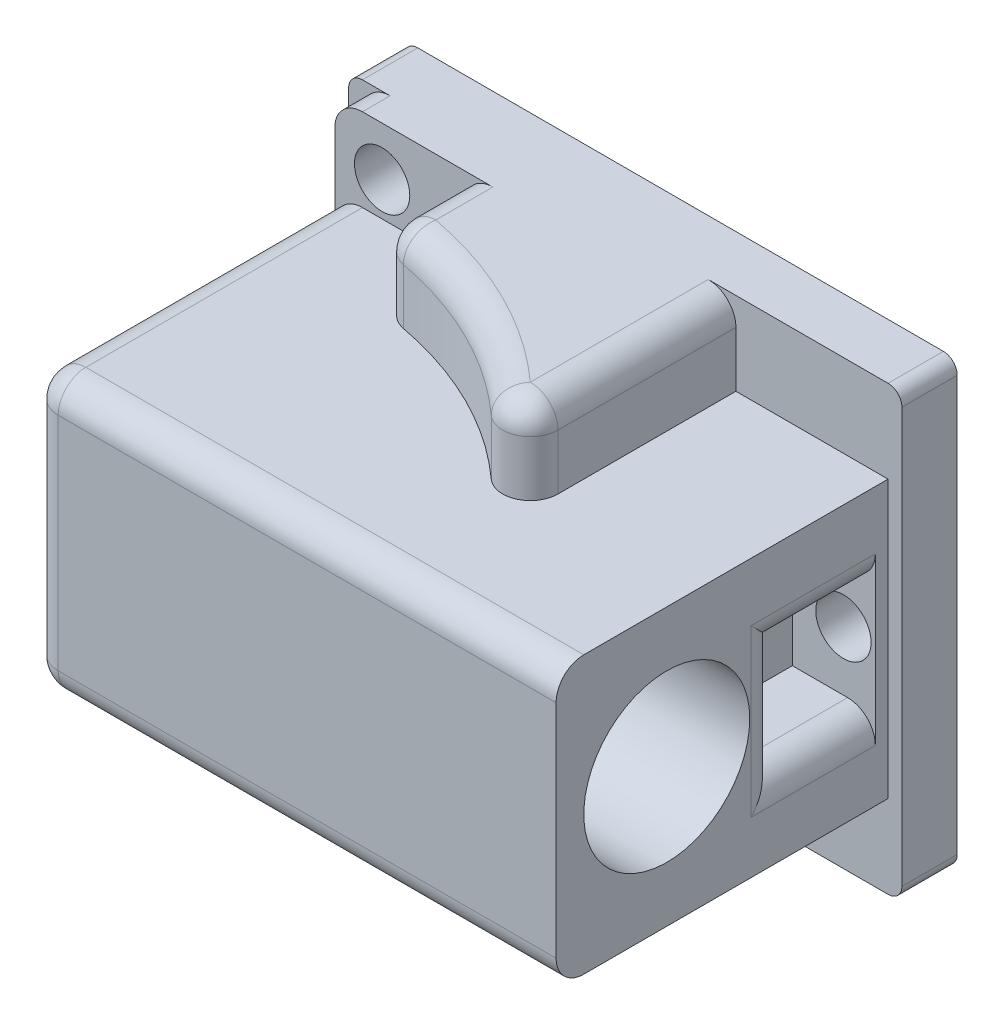
SolidWorks part; units mm, degrees
ref_plane "Front Plane" through (0, 0, 0) normal (0, 0, 1) x (1, 0, 0)
ref_plane "Top Plane" through (0, 0, 0) normal (0, 1, 0) x (1, 0, 0)
ref_plane "Right Plane" through (0, 0, 0) normal (1, 0, 0) x (0, 0, -1)
ref_plane "Plane1" through (0, 50, 0) normal (0, 1, 0) x (1, 0, 0)
sketch "Sketch1" plane through (0, 50, 0) normal (0, 1, 0) x (1, 0, 0)
  line L0 (-95, 0) -> (-95, -110)
  line L1 (-95, -110) -> (40, -110)
  line L2 (40, -110) -> (40, 0)
  line L3 (40, 0) -> (-95, 0)
extrude "Boss-Extrude1" add sketch "Sketch1" against normal blind 100
sketch "Sketch2" plane through (0, 50, 0) normal (0, 1, 0) x (-1, 0, 0)
  line L0 (-40, 0) -> (-40, 110)
  line L1 (95, 61.9894) -> (95, 0)
  line L2 (95, 0) -> (-40, 0)
  arc A0 (-40, 110) -> (95, 61.9894) centre (63.8483, 188.2018) ccw
extrude "Boss-Extrude2" add sketch "Sketch2" along normal blind 30
sketch "Sketch3" plane through (0, -50, 0) normal (0, -1, 0) x (1, 0, 0)
  line L0 (40, 0) -> (-95, 0)
  line L1 (-95, 0) -> (-95, 61.9894)
  line L2 (40, 110) -> (40, 0)
  arc A0 (-95, 61.9894) -> (40, 110) centre (-63.8483, 188.2018) ccw
extrude "Boss-Extrude3" add sketch "Sketch3" along normal blind 30
sketch "Sketch4" plane through (0, 0, 110) normal (0, 0, 1) x (1, 0, 0)
  line L0 (40, -50) -> (-95, -50)
  line L1 (-95, -50) -> (-95, 50)
  line L2 (-95, 50) -> (40, 50)
  line L3 (40, 50) -> (40, -50)
extrude "Boss-Extrude4" add sketch "Sketch4" along normal blind 30
sketch "Sketch5" plane through (40, 0, 0) normal (1, 0, 0) x (0, 0, -1)
  line L0 (-140, 50) -> (-20, 50)
  line L1 (-20, 50) -> (-20, 80)
  line L2 (-20, 80) -> (0, 80)
  line L3 (0, 80) -> (0, -80)
  line L4 (0, -80) -> (-20, -80)
  line L5 (-20, -80) -> (-20, -50)
  line L6 (-20, -50) -> (-140, -50)
  line L7 (-140, -50) -> (-140, 50)
extrude "Boss-Extrude5" add sketch "Sketch5" along normal blind 55
sketch "Sketch6" plane through (-95, 0, 0) normal (-1, 0, 0) x (0, 0, 1)
  line L0 (0, -80) -> (0, 80)
  line L1 (0, 80) -> (20, 80)
  line L2 (20, 80) -> (20, -80)
  line L3 (20, -80) -> (0, -80)
extrude "Boss-Extrude6" add sketch "Sketch6" along normal blind 5
sketch "Sketch7" plane through (95, 0, 0) normal (1, 0, 0) x (0, 0, -1)
  line L0 (-20, -80) -> (-20, 80)
  line L1 (-20, 80) -> (0, 80)
  line L2 (0, 80) -> (0, -80)
  line L3 (0, -80) -> (-20, -80)
extrude "Boss-Extrude7" add sketch "Sketch7" along normal blind 5
sketch "Sketch8" plane through (0, 80, 0) normal (0, 1, 0) x (-1, 0, 0)
  line L0 (47.8742, 59.187) -> (47.8742, 30)
  line L1 (47.8742, 30) -> (95, 30)
  line L2 (95, 30) -> (95, 61.9894)
  arc A0 (95, 61.9894) -> (47.8742, 59.187) centre (63.8483, 188.2018) cw
extrude "Cut-Extrude1" cut sketch "Sketch8" against normal blind 30
sketch "Sketch9" plane through (0, -80, 0) normal (0, -1, 0) x (1, 0, 0)
  line L0 (-47.8742, 30) -> (-47.8742, 59.187)
  line L1 (-95, 61.9894) -> (-95, 30)
  line L2 (-95, 30) -> (-47.8742, 30)
  arc A0 (-47.8742, 59.187) -> (-95, 61.9894) centre (-63.8483, 188.2018) cw
extrude "Cut-Extrude2" cut sketch "Sketch9" against normal blind 30
sketch "Sketch10" plane through (95, 0, 0) normal (1, 0, 0) x (0, 0, -1)
  line L0 (-24.6023, -21.1021) -> (-24.6023, 18.8979)
  line L1 (-24.6023, 18.8979) -> (-59.6023, 18.8979)
  line L2 (-59.6023, 18.8979) -> (-59.6023, -21.1021)
  line L3 (-59.6023, -21.1021) -> (-24.6023, -21.1021)
extrude "Cut-Extrude3" cut sketch "Sketch10" against normal blind 30
hole_wizard "Hole1" positions "Sketch12" profile "Sketch11" legacy
sketch "Sketch12" plane through (0, 0, 0) normal (0, 0, -1) x (-1, 0, 0)
  point P0 (0, 0)
sketch "Sketch11" plane through (0, 0, 0) normal (1, 0, 0) x (0, 1, 0)
  line L0 (0, 0) -> (0, 135)
  line L1 (0, 135) -> (40, 135)
  line L2 (40, 135) -> (40, 0)
  line L3 (40, 0) -> (0, 0)
  line L4 (0, 110) -> (0, -10) construction
  dimension "Diameter" = 80
  dimension "Depth" = 135
hole_wizard "Hole2" positions "Sketch14" profile "Sketch13" legacy
sketch "Sketch14" plane through (95, 0, 0) normal (1, 0, 0) x (0, 0, -1)
  point P0 (-100, 0)
sketch "Sketch13" plane through (95, 0, 100) normal (0, 1, 0) x (0, 0, -1)
  line L0 (0, 0) -> (0, 55)
  line L1 (0, 55) -> (30, 55)
  line L2 (30, 55) -> (30, 0)
  line L3 (30, 0) -> (0, 0)
  line L4 (0, 110) -> (0, -10) construction
  dimension "Diameter" = 60
  dimension "Depth" = 55
hole_wizard "3/4 Clearance Hole1" positions "Sketch16" profile "Sketch15" hole size "3/4" standard "ANSI Inch"
sketch "Sketch16" plane through (0, 0, 24.6023) normal (0, 0, 1) x (1, 0, 0)
  point P0 (83.46, 0.37)
sketch "Sketch15" plane through (83.46, 0.37, 24.6023) normal (1, 0, 0) x (0, -1, 0)
  line L0 (0, 0) -> (0, 24.6023)
  line L1 (0, 24.6023) -> (10, 24.6023)
  line L2 (10, 24.6023) -> (10, 0)
  line L5 (10, 0) -> (0, 0)
  line L11 (0, -6.35) -> (0, 107.95) construction
  dimension "Thru Hole Dia." = 20
  dimension "Thru Hole Depth" = 24.6023
hole_wizard "3/4 Clearance Hole2" positions "Sketch18" profile "Sketch17" hole size "3/4" standard "ANSI Inch"
sketch "Sketch18" plane through (0, 0, 30) normal (0, 0, 1) x (1, 0, 0)
  point P0 (-77.8954, -62.3163)
  point P1 (-77.8954, 62.3163)
sketch "Sketch17" plane through (-77.8954, -62.3163, 30) normal (1, 0, 0) x (0, -1, 0)
  line L0 (0, 0) -> (0, 30)
  line L1 (0, 30) -> (10, 30)
  line L2 (10, 30) -> (10, 0)
  line L5 (10, 0) -> (0, 0)
  line L11 (0, -6.35) -> (0, 107.95) construction
  dimension "Thru Hole Dia." = 20
  dimension "Thru Hole Depth" = 30
fillet "Fillet1" radius 5 4 edges at (-100, 80, 10) (100, 80, 10) (100, -80, 10) (-100, -80, 10)
fillet "Fillet2" radius 10 20 edges at (-95, 50, 85) (0, 50, 140) (-95, -50, 85) (-95, -80, 25) (-95, 0, 140) (0, -50, 140) (40, 65, 110) (40, 80, 65) (-47.8742, 65, 59.187) (1.2274, 80, 75.6623) (-47.8742, 80, 44.5935) (95, -21.1021, 42.1023) (95, -1.1021, 59.6023) (95, 18.8979, 42.1023) (40, -65, 110) (40, -80, 65) (1.2274, -80, 75.6623) (-47.8742, -80, 44.5935) (-47.8742, -65, 59.187) (-95, 80, 25)
